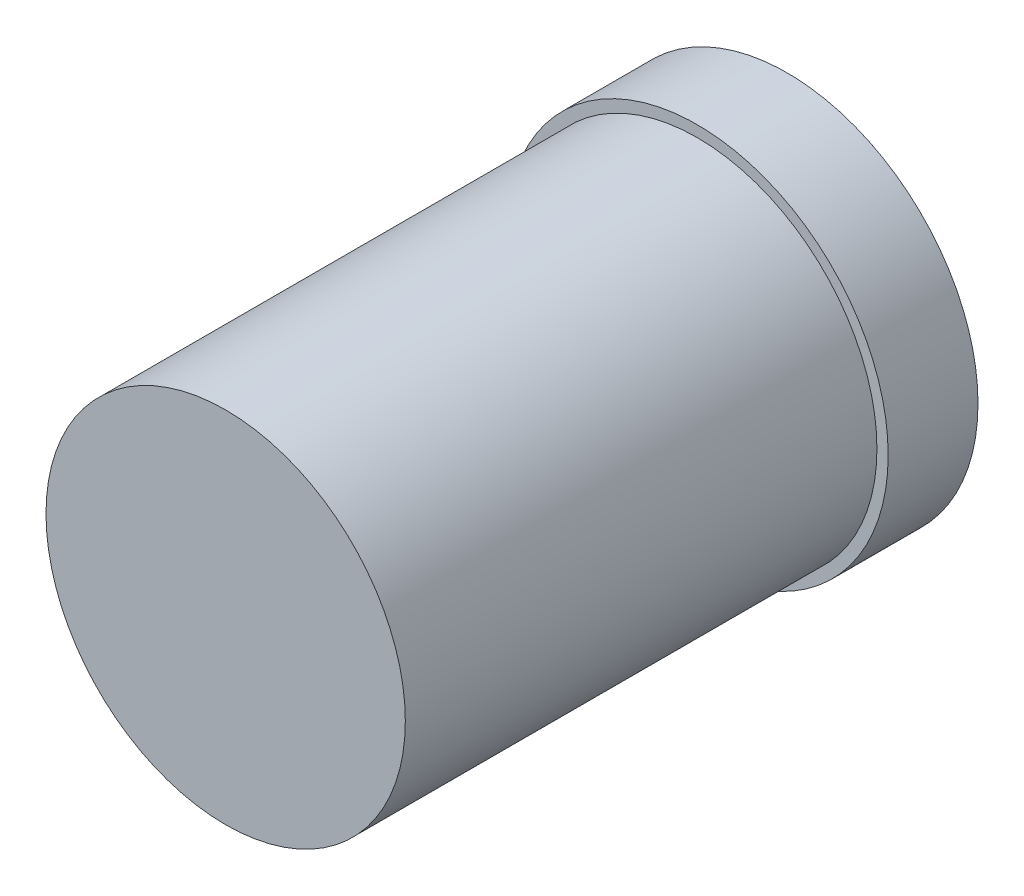
SolidWorks part; units mm, degrees
ref_plane "Front Plane" through (0, 0, 0) normal (0, 0, 1) x (1, 0, 0)
ref_plane "Top Plane" through (0, 0, 0) normal (0, 1, 0) x (1, 0, 0)
ref_plane "Right Plane" through (0, 0, 0) normal (1, 0, 0) x (0, 0, -1)
sketch "Sketch1" plane through (0, 0, 0) normal (0, 0, 1) x (1, 0, 0)
  circle A0 centre (0, 0) radius 85
  dimension "D1" = 170
extrude "Boss-Extrude2" add sketch "Sketch1" along normal blind 40
sketch "Sketch3" plane through (0, 0, 40) normal (0, 0, 1) x (1, 0, 0)
  circle A0 centre (0, 0) radius 80
  dimension "D1" = 160
extrude "Boss-Extrude3" add sketch "Sketch3" along normal blind 40
sketch "Sketch4" plane through (0, 0, 80) normal (0, 0, 1) x (1, 0, 0)
  circle A0 centre (0, 0) radius 80
  dimension "D1" = 160
extrude "Boss-Extrude4" add sketch "Sketch4" along normal blind 170 contours A0
